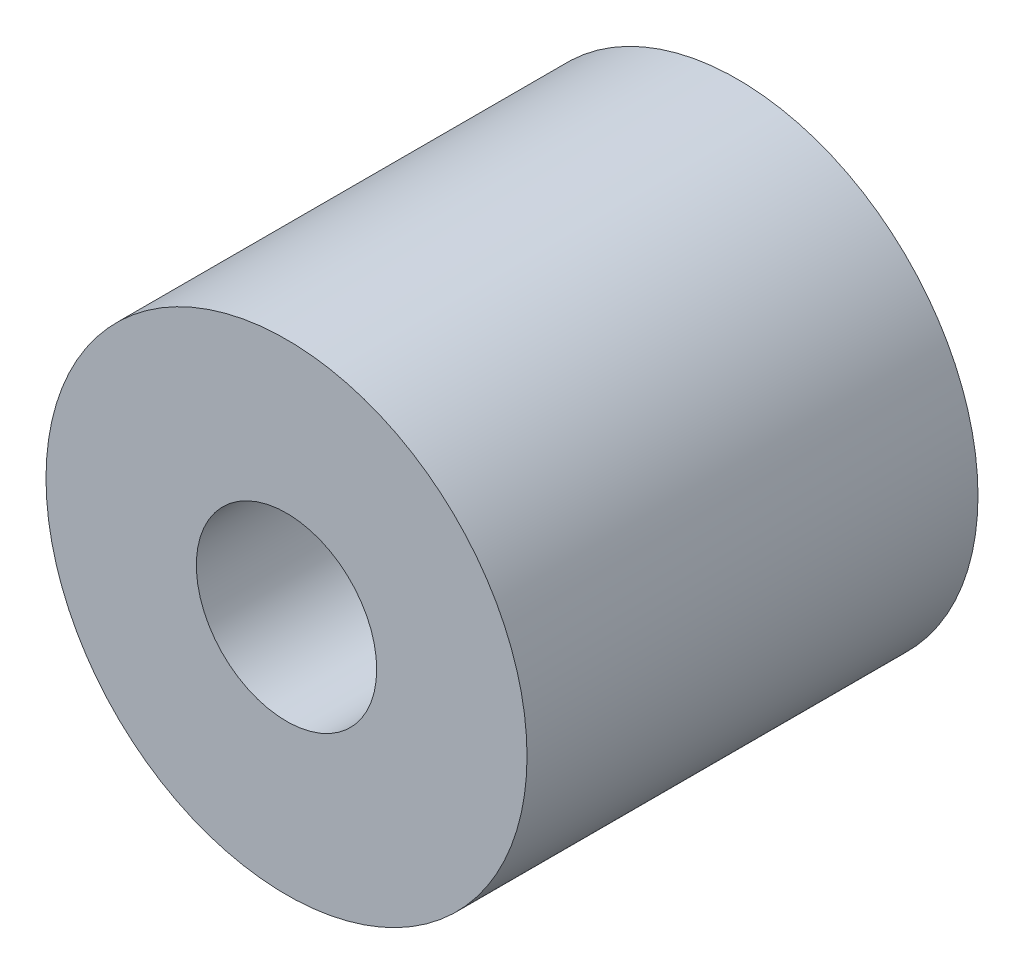
SolidWorks part; units mm, degrees
material "AISI 304"
ref_plane "Plano frontal" through (0, 0, 0) normal (0, 0, 1) x (1, 0, 0)
ref_plane "Plano superior" through (0, 0, 0) normal (0, 1, 0) x (1, 0, 0)
ref_plane "Plano direito" through (0, 0, 0) normal (1, 0, 0) x (0, 0, -1)
sketch "Esboço1" plane through (0, 0, 0) normal (0, 0, 1) x (1, 0, 0)
  circle A0 centre (0, 0) radius 3
  circle A1 centre (0, 0) radius 8
  dimension "D1" = 6
  dimension "D2" = 16
extrude "Ressalto-extrusão1" add sketch "Esboço1" along normal mid plane 15 contours A1
